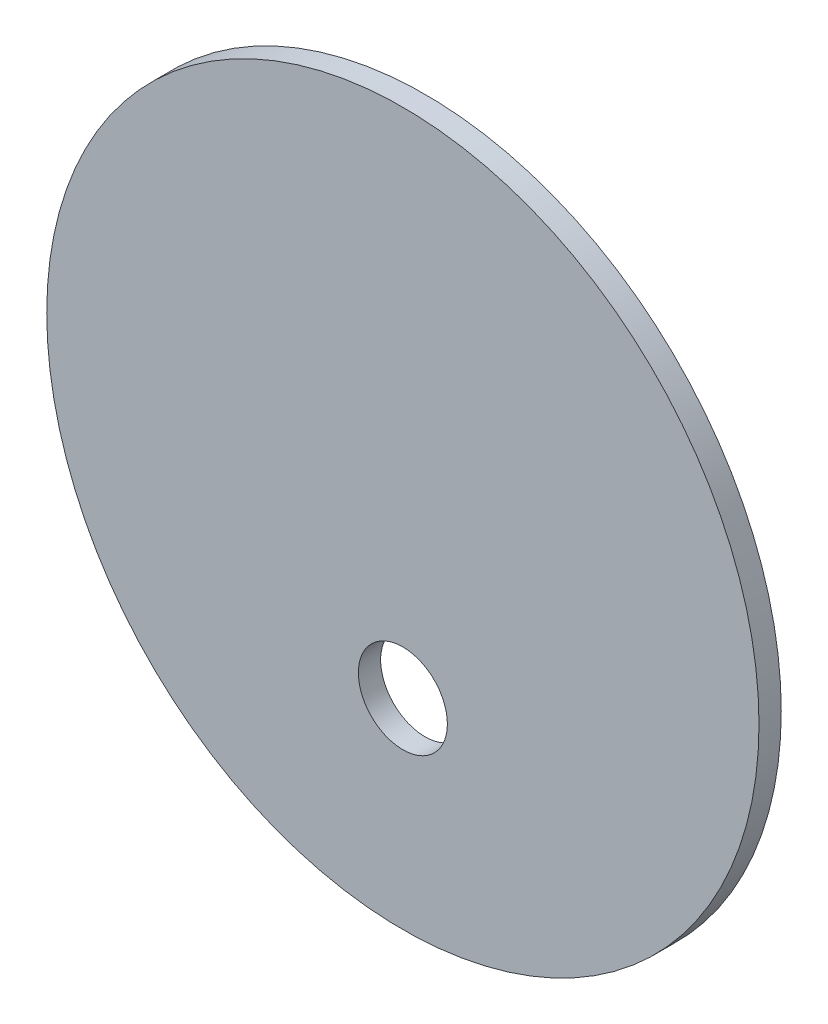
SolidWorks part; units mm, degrees
material "ABS"
ref_plane "Front Plane" through (0, 0, 0) normal (0, 0, 1) x (1, 0, 0)
ref_plane "Top Plane" through (0, 0, 0) normal (0, 1, 0) x (1, 0, 0)
ref_plane "Right Plane" through (0, 0, 0) normal (1, 0, 0) x (0, 0, -1)
sketch "Sketch1" plane through (0, 0, 0) normal (0, 0, 1) x (1, 0, 0)
  circle A0 centre (0, 0) radius 80
  dimension "D1" = 160
extrude "Boss-Extrude1" add sketch "Sketch1" along normal blind 5
sketch "Sketch2" plane through (0, 0, 5) normal (0, 0, 1) x (1, 0, 0)
  circle A2 centre (0, -35) radius 10
  circle A3 centre (0, 0) radius 80 construction
  point P3 (0, -35.1028)
  dimension "D1" = 20
  dimension "D2" = 35
extrude "Cut-Extrude2" cut sketch "Sketch2" against normal blind 20
